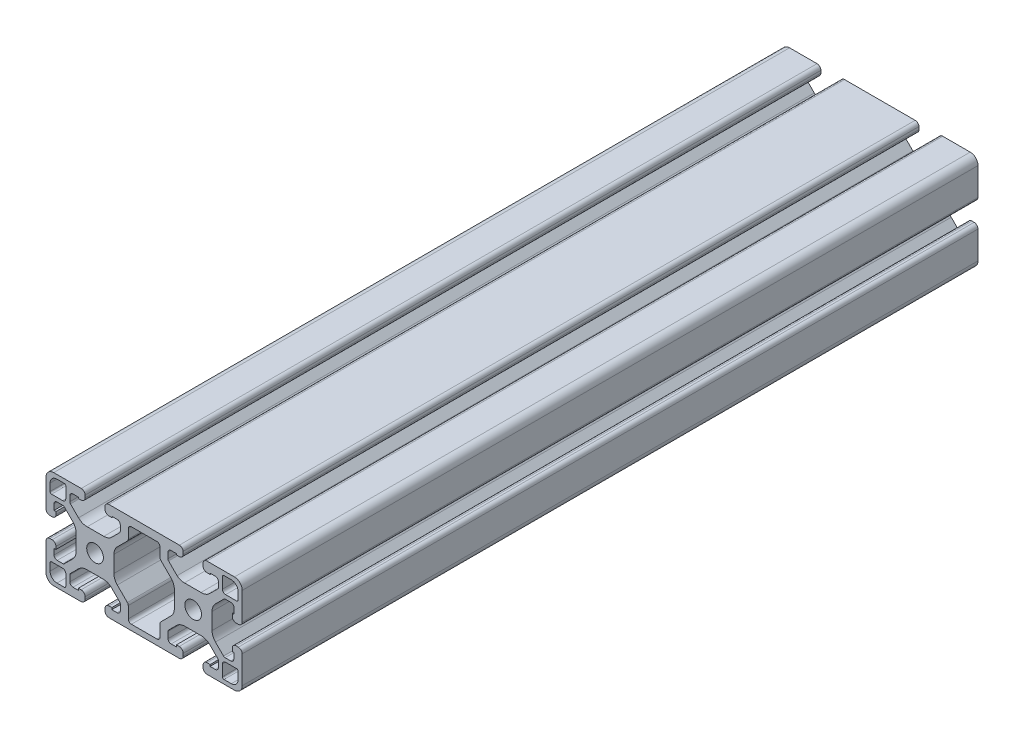
SolidWorks part; units mm, degrees
material "6105-T5 Aluminum"
ref_plane "Front Plane" through (0, 0, 0) normal (0, 0, 1) x (1, 0, 0)
ref_plane "Top Plane" through (0, 0, 0) normal (0, 1, 0) x (1, 0, 0)
ref_plane "Right Plane" through (0, 0, 0) normal (1, 0, 0) x (0, 0, -1)
sketch "Sketch1" plane through (0, 0, 0) normal (0, 0, 1) x (1, 0, 0)
  line L0 (0, 20) -> (0, -20) construction
  line L1 (-14.38, 20) -> (14.38, 20)
  line L2 (-30.0243, -12.1998) -> (-26.7392, -8.9146)
  line L3 (-15.94, 17.51) -> (-15.94, 18.6069)
  line L4 (-10.9397, -6.7352) -> (-6.8324, -10.8426)
  line L5 (-12.3247, 3.3825) -> (-12.3289, -3.3756)
  line L6 (-6.8214, 10.8451) -> (-10.9313, 6.7404)
  line L7 (-6.4494, 15.43) -> (-6.4494, 11.7432)
  line L8 (0, 16.6968) -> (-5.1794, 16.7)
  line L9 (-14.37, 15.94) -> (-13.1517, 15.94)
  line L10 (-13.1517, 16.4117) -> (-13.1517, 15.94)
  line L11 (-5.1904, -17.7174) -> (5.1904, -17.7174)
  line L12 (-6.4604, -16.4474) -> (-6.4604, -11.7406)
  line L13 (-13.1517, 16.4117) -> (-11.0437, 16.4117)
  line L14 (-9.715, 12.8476) -> (-9.715, 15.1433)
  line L15 (-13.4586, 8.7397) -> (-9.9761, 12.2179)
  line L16 (-23.1872, 7.7) -> (-16.4312, 7.7)
  line L17 (-37.72, 11.94) -> (-33.21, 11.94)
  line L18 (-31.935, 13.21) -> (-31.935, 17.72)
  line L19 (-35.545, 18.35) -> (-32.565, 18.35)
  line L20 (-38.345, 15.55) -> (-38.345, 12.57)
  line L21 (-26.7456, 9.087) -> (-30.0243, 12.3658)
  line L22 (-30.285, 12.9951) -> (-30.285, 15.0869)
  line L23 (-29.015, 16.3569) -> (-26.8483, 16.3569)
  line L24 (-26.8483, 16.3569) -> (-26.8483, 15.8852)
  line L25 (-26.8483, 15.8852) -> (-25.63, 15.8852)
  line L26 (-24.06, 17.4552) -> (-24.06, 18.43)
  line L27 (-36.83, 20) -> (-25.63, 20)
  line L28 (-31.935, -17.72) -> (-31.935, -13.21)
  line L29 (-40, 16.83) -> (-40, 13)
  line L30 (-40, 5.5719) -> (-40, 13)
  line L31 (-38.43, 4.06) -> (-37.51, 4.06)
  line L32 (-35.94, 5.63) -> (-35.94, 6.6964)
  line L33 (-36.715, 6.6964) -> (-35.94, 6.6964)
  line L34 (-36.715, 6.6964) -> (-36.715, 9.02)
  line L35 (-35.445, 10.29) -> (-33.1501, 10.29)
  line L36 (-32.5208, 10.0293) -> (-29.0912, 6.5998)
  line L37 (-27.7, 3.241) -> (-27.7, -3.241)
  line L38 (-32.5208, -10.0293) -> (-29.0912, -6.5998)
  line L39 (-35.445, -10.29) -> (-33.1501, -10.29)
  line L40 (-36.715, -9.02) -> (-36.715, -6.6964)
  line L41 (-35.94, -6.6964) -> (-36.715, -6.6964)
  line L42 (-35.94, -6.6964) -> (-35.94, -5.63)
  line L43 (-38.43, -4.06) -> (-37.51, -4.06)
  line L44 (-40, -16.83) -> (-40, -5.5719)
  line L45 (-37.72, -11.94) -> (-33.21, -11.94)
  line L46 (-36.83, -20) -> (-25.6944, -20)
  line L47 (-14.3056, -20) -> (-6.9396, -20)
  line L48 (-29.015, -16.5584) -> (-26.8283, -16.5584)
  line L49 (-24.06, -17.4474) -> (-24.06, -18.3656)
  line L50 (-26.8283, -15.813) -> (-25.6944, -15.813)
  line L51 (-26.8283, -16.5584) -> (-26.8283, -15.813)
  line L52 (-30.285, -15.2884) -> (-30.285, -12.8291)
  line L53 (25.63, 20) -> (34.2818, 20)
  line L54 (-23.3834, -7.5234) -> (-16.6166, -7.5234)
  line L55 (-13.2608, -8.9146) -> (-9.9757, -12.1998)
  line L56 (-9.715, -12.8291) -> (-9.715, -15.3686)
  line L57 (-13.1717, -16.5584) -> (-11.0293, -16.5584)
  line L58 (-13.1717, -16.5584) -> (-13.1717, -15.813)
  line L59 (-14.3056, -15.813) -> (-13.1717, -15.813)
  line L60 (-15.94, -17.4474) -> (-15.94, -18.3656)
  line L61 (-6.9396, -20) -> (6.9396, -20)
  line L62 (6.9396, -20) -> (14.3056, -20)
  line L63 (-39.8916, 0) -> (0, 0) construction
  line L64 (25.6944, -20) -> (34.3223, -20)
  line L65 (15.94, -17.4474) -> (15.94, -18.3656)
  line L66 (13.1717, -15.813) -> (14.3056, -15.813)
  line L67 (13.1717, -16.5584) -> (13.1717, -15.813)
  line L68 (11.0293, -16.5584) -> (13.1717, -16.5584)
  line L69 (9.715, -12.8291) -> (9.715, -15.3686)
  line L70 (9.9757, -12.1998) -> (13.2608, -8.9146)
  line L71 (23.3834, -7.5234) -> (16.6166, -7.5234)
  line L72 (30.0243, -12.1998) -> (26.7392, -8.9146)
  line L73 (30.285, -15.2884) -> (30.285, -12.8291)
  line L74 (26.907, -16.5584) -> (29.015, -16.5584)
  line L75 (26.907, -15.8852) -> (26.907, -16.5584)
  line L76 (25.63, -15.8852) -> (26.907, -15.8852)
  line L77 (24.06, -18.43) -> (24.06, -17.4552)
  line L78 (6.8214, 10.8451) -> (10.9313, 6.7404)
  line L79 (36.83, -20) -> (34.3223, -20)
  line L80 (40, -16.83) -> (40, -5.5696)
  line L81 (40, 5.5719) -> (40, 13)
  line L82 (37.51, -3.9996) -> (38.43, -3.9996)
  line L83 (35.94, -6.7799) -> (35.94, -5.5696)
  line L84 (36.5725, -6.7799) -> (35.94, -6.7799)
  line L85 (36.5725, -9.1555) -> (36.5725, -6.7799)
  line L86 (33.0076, -10.4255) -> (35.3025, -10.4255)
  line L87 (29.0891, -6.8716) -> (32.3778, -10.1644)
  line L88 (27.7, 3.241) -> (27.7, -3.515)
  line L89 (32.5208, 10.0293) -> (29.0912, 6.5998)
  line L90 (35.445, 10.29) -> (33.1501, 10.29)
  line L91 (36.715, 6.6964) -> (36.715, 9.02)
  line L92 (35.94, 6.6964) -> (36.715, 6.6964)
  line L93 (35.94, 5.63) -> (35.94, 6.6964)
  line L94 (38.43, 4.06) -> (37.51, 4.06)
  line L95 (38.345, -15.55) -> (38.345, -12.57)
  line L96 (40, 16.83) -> (40, 13)
  line L97 (34.2818, 20) -> (36.83, 20)
  line L98 (31.935, -17.72) -> (31.935, -13.21)
  line L99 (24.06, 17.4552) -> (24.06, 18.43)
  line L100 (26.8483, 15.8852) -> (25.63, 15.8852)
  line L101 (26.8483, 16.3569) -> (26.8483, 15.8852)
  line L102 (29.015, 16.3569) -> (26.8483, 16.3569)
  line L103 (30.285, 12.9951) -> (30.285, 15.0869)
  line L104 (26.7456, 9.087) -> (30.0243, 12.3658)
  line L105 (38.345, 15.55) -> (38.345, 12.57)
  line L106 (32.565, 18.35) -> (35.545, 18.35)
  line L107 (31.935, 13.21) -> (31.935, 17.72)
  line L108 (37.72, 11.94) -> (33.21, 11.94)
  line L109 (23.1872, 7.7) -> (16.4312, 7.7)
  line L110 (13.4586, 8.7397) -> (9.9761, 12.2179)
  line L111 (9.715, 12.8476) -> (9.715, 15.1433)
  line L112 (11.0437, 16.4117) -> (13.1517, 16.4117)
  line L113 (6.4604, -16.4474) -> (6.4604, -11.7406)
  line L114 (-38.345, -15.55) -> (-38.345, -12.57)
  line L115 (13.1517, 16.4117) -> (13.1517, 15.94)
  line L116 (13.1517, 15.94) -> (14.37, 15.94)
  line L117 (0, 16.6968) -> (5.1794, 16.7)
  line L118 (6.4494, 15.43) -> (6.4494, 11.7432)
  line L119 (-35.545, -18.35) -> (-32.565, -18.35)
  line L120 (12.3247, 3.3825) -> (12.3289, -3.3756)
  line L121 (10.9397, -6.7352) -> (6.8324, -10.8426)
  line L122 (15.94, 17.51) -> (15.94, 18.6069)
  line L129 (37.72, -11.94) -> (33.21, -11.94)
  line L131 (32.565, -18.35) -> (35.545, -18.35)
  line L133 (-20, 11.7412) -> (-20, -12.5149) construction
  line L134 (20, 12.6864) -> (20, -12.5149) construction
  line L135 (-20, 0) -> (-47.3415, -27.3415) construction
  arc A0 (-15.94, 18.6069) -> (-14.38, 20) centre (-14.38, 18.43) cw
  circle A1 centre (-20, 0) radius 3.4
  arc A2 (-14.37, 15.94) -> (-15.94, 17.51) centre (-14.37, 17.51) cw
  arc A3 (-11.0437, 16.4117) -> (-9.715, 15.1433) centre (-10.985, 15.1431) cw
  arc A4 (-13.4586, 8.7397) -> (-16.4312, 7.7) centre (-16.4245, 12.45) cw
  arc A5 (-23.1872, 7.7) -> (-26.7456, 9.087) centre (-23.3868, 12.4458) cw
  arc A6 (-12.3289, -3.3756) -> (-10.9397, -6.7352) centre (-7.5789, -3.3786) ccw
  arc A7 (-10.9313, 6.7404) -> (-12.3247, 3.3825) centre (-7.5747, 3.3795) ccw
  arc A8 (-6.8214, 10.8451) -> (-6.4494, 11.7432) centre (-7.7194, 11.7432) ccw
  arc A9 (-5.1794, 16.7) -> (-6.4494, 15.43) centre (-5.1794, 15.43) ccw
  arc A10 (-9.715, 12.8476) -> (-9.9761, 12.2179) centre (-10.605, 12.8476) cw
  arc A11 (-6.4604, -16.4474) -> (-5.1904, -17.7174) centre (-5.1904, -16.4474) ccw
  arc A12 (-6.4604, -11.7406) -> (-6.8324, -10.8426) centre (-7.7304, -11.7406) ccw
  arc A13 (-33.21, 11.94) -> (-31.935, 13.21) centre (-33.205, 13.21) ccw
  arc A14 (-31.935, 17.72) -> (-32.565, 18.35) centre (-32.565, 17.72) ccw
  arc A15 (-35.545, 18.35) -> (-38.345, 15.55) centre (-35.545, 15.55) ccw
  arc A16 (-38.345, 12.57) -> (-37.72, 11.94) centre (-37.715, 12.57) ccw
  arc A17 (-30.285, 12.9951) -> (-30.0243, 12.3658) centre (-29.395, 12.9951) ccw
  arc A18 (-29.015, 16.3569) -> (-30.285, 15.0869) centre (-29.015, 15.0869) ccw
  arc A19 (-25.63, 15.8852) -> (-24.06, 17.4552) centre (-25.63, 17.4552) ccw
  arc A20 (-24.06, 18.43) -> (-25.63, 20) centre (-25.63, 18.43) ccw
  arc A21 (-36.83, 20) -> (-40, 16.83) centre (-36.83, 16.83) ccw
  arc A22 (-40, 5.5719) -> (-38.43, 4.06) centre (-38.4311, 5.63) ccw
  arc A23 (-37.51, 4.06) -> (-35.94, 5.63) centre (-37.51, 5.63) ccw
  arc A24 (-35.445, 10.29) -> (-36.715, 9.02) centre (-35.445, 9.02) ccw
  arc A25 (-32.5208, 10.0293) -> (-33.1501, 10.29) centre (-33.1501, 9.4) ccw
  arc A26 (-27.7, 3.241) -> (-29.0912, 6.5998) centre (-32.45, 3.241) ccw
  arc A27 (-27.7, -3.241) -> (-29.0912, -6.5998) centre (-32.45, -3.241) cw
  arc A28 (-32.5208, -10.0293) -> (-33.1501, -10.29) centre (-33.1501, -9.4) cw
  arc A29 (-35.445, -10.29) -> (-36.715, -9.02) centre (-35.445, -9.02) cw
  arc A30 (-37.51, -4.06) -> (-35.94, -5.63) centre (-37.51, -5.63) cw
  arc A31 (-40, -5.5719) -> (-38.43, -4.06) centre (-38.4311, -5.63) cw
  arc A32 (-40, -16.83) -> (-36.83, -20) centre (-36.83, -16.83) ccw
  arc A33 (-24.06, -18.3656) -> (-25.6944, -20) centre (-25.6944, -18.3656) cw
  arc A34 (-25.6944, -15.813) -> (-24.06, -17.4474) centre (-25.6944, -17.4474) cw
  arc A35 (-30.285, -15.2884) -> (-29.015, -16.5584) centre (-29.015, -15.2884) ccw
  arc A36 (-30.0243, -12.1998) -> (-30.285, -12.8291) centre (-29.395, -12.8291) ccw
  arc A37 (-23.3834, -7.5234) -> (-26.7392, -8.9146) centre (-23.3804, -12.2734) ccw
  arc A38 (-13.2608, -8.9146) -> (-16.6166, -7.5234) centre (-16.6196, -12.2734) ccw
  arc A39 (-9.715, -12.8291) -> (-9.9757, -12.1998) centre (-10.605, -12.8291) ccw
  arc A40 (-11.0293, -16.5584) -> (-9.715, -15.3686) centre (-10.9825, -15.2892) ccw
  arc A41 (-14.3056, -15.813) -> (-15.94, -17.4474) centre (-14.3056, -17.4474) ccw
  arc A42 (-15.94, -18.3656) -> (-14.3056, -20) centre (-14.3056, -18.3656) ccw
  arc A43 (15.94, -18.3656) -> (14.3056, -20) centre (14.3056, -18.3656) cw
  arc A44 (14.3056, -15.813) -> (15.94, -17.4474) centre (14.3056, -17.4474) cw
  arc A45 (11.0293, -16.5584) -> (9.715, -15.3686) centre (10.9825, -15.2892) cw
  arc A46 (9.715, -12.8291) -> (9.9757, -12.1998) centre (10.605, -12.8291) cw
  arc A47 (13.2608, -8.9146) -> (16.6166, -7.5234) centre (16.6196, -12.2734) cw
  arc A48 (23.3834, -7.5234) -> (26.7392, -8.9146) centre (23.3804, -12.2734) cw
  arc A49 (30.0243, -12.1998) -> (30.285, -12.8291) centre (29.395, -12.8291) cw
  arc A50 (30.285, -15.2884) -> (29.015, -16.5584) centre (29.015, -15.2884) cw
  arc A51 (24.06, -17.4552) -> (25.63, -15.8852) centre (25.63, -17.4552) cw
  arc A52 (25.6944, -20) -> (24.06, -18.43) centre (25.63, -18.4313) cw
  arc A53 (40, -16.83) -> (36.83, -20) centre (36.83, -16.83) cw
  arc A54 (38.43, -3.9996) -> (40, -5.5696) centre (38.43, -5.5696) cw
  arc A55 (35.94, -5.5696) -> (37.51, -3.9996) centre (37.51, -5.5696) cw
  arc A56 (36.5725, -9.1555) -> (35.3025, -10.4255) centre (35.3025, -9.1555) cw
  arc A57 (33.0076, -10.4255) -> (32.3778, -10.1644) centre (33.0076, -9.5355) cw
  arc A58 (29.0891, -6.8716) -> (27.7, -3.515) centre (32.45, -3.515) cw
  arc A59 (27.7, 3.241) -> (29.0912, 6.5998) centre (32.45, 3.241) cw
  arc A60 (32.5208, 10.0293) -> (33.1501, 10.29) centre (33.1501, 9.4) cw
  arc A61 (35.445, 10.29) -> (36.715, 9.02) centre (35.445, 9.02) cw
  arc A62 (37.51, 4.06) -> (35.94, 5.63) centre (37.51, 5.63) cw
  arc A63 (40, 5.5719) -> (38.43, 4.06) centre (38.4311, 5.63) cw
  arc A64 (36.83, 20) -> (40, 16.83) centre (36.83, 16.83) cw
  arc A65 (24.06, 18.43) -> (25.63, 20) centre (25.63, 18.43) cw
  arc A66 (25.63, 15.8852) -> (24.06, 17.4552) centre (25.63, 17.4552) cw
  arc A67 (29.015, 16.3569) -> (30.285, 15.0869) centre (29.015, 15.0869) cw
  arc A68 (30.285, 12.9951) -> (30.0243, 12.3658) centre (29.395, 12.9951) cw
  arc A69 (38.345, 12.57) -> (37.72, 11.94) centre (37.715, 12.57) cw
  arc A70 (35.545, 18.35) -> (38.345, 15.55) centre (35.545, 15.55) cw
  arc A71 (31.935, 17.72) -> (32.565, 18.35) centre (32.565, 17.72) cw
  arc A72 (33.21, 11.94) -> (31.935, 13.21) centre (33.205, 13.21) cw
  arc A73 (6.4604, -11.7406) -> (6.8324, -10.8426) centre (7.7304, -11.7406) cw
  arc A74 (6.4604, -16.4474) -> (5.1904, -17.7174) centre (5.1904, -16.4474) cw
  arc A75 (9.715, 12.8476) -> (9.9761, 12.2179) centre (10.605, 12.8476) ccw
  arc A76 (5.1794, 16.7) -> (6.4494, 15.43) centre (5.1794, 15.43) cw
  arc A77 (6.8214, 10.8451) -> (6.4494, 11.7432) centre (7.7194, 11.7432) cw
  arc A78 (10.9313, 6.7404) -> (12.3247, 3.3825) centre (7.5747, 3.3795) cw
  arc A79 (12.3289, -3.3756) -> (10.9397, -6.7352) centre (7.5789, -3.3786) cw
  arc A80 (23.1872, 7.7) -> (26.7456, 9.087) centre (23.3868, 12.4458) ccw
  arc A81 (13.4586, 8.7397) -> (16.4312, 7.7) centre (16.4245, 12.45) ccw
  arc A82 (11.0437, 16.4117) -> (9.715, 15.1433) centre (10.985, 15.1431) ccw
  arc A83 (14.37, 15.94) -> (15.94, 17.51) centre (14.37, 17.51) ccw
  circle A84 centre (20, 0) radius 3.4
  arc A85 (15.94, 18.6069) -> (14.38, 20) centre (14.38, 18.43) ccw
  arc A86 (-38.345, -12.57) -> (-37.72, -11.94) centre (-37.715, -12.57) cw
  arc A87 (-35.545, -18.35) -> (-38.345, -15.55) centre (-35.545, -15.55) cw
  arc A88 (-31.935, -17.72) -> (-32.565, -18.35) centre (-32.565, -17.72) cw
  arc A89 (-33.21, -11.94) -> (-31.935, -13.21) centre (-33.205, -13.21) cw
  arc A90 (33.21, -11.94) -> (31.935, -13.21) centre (33.205, -13.21) ccw
  arc A91 (31.935, -17.72) -> (32.565, -18.35) centre (32.565, -17.72) ccw
  arc A92 (35.545, -18.35) -> (38.345, -15.55) centre (35.545, -15.55) ccw
  arc A93 (38.345, -12.57) -> (37.72, -11.94) centre (37.715, -12.57) ccw
  dimension "D2" = 6.8
  dimension "D1" = 40
  dimension "D3" = 40
  dimension "D4" = 8.12
  dimension "D5" = 80
  dimension "D6" = 3.3
  dimension "D7" = 12.3
  dimension "D8" = 45
  dimension "D9" = 20.57
  dimension "D10" = 4.06
  dimension "D15" = 1.5145
  dimension "D16" = 1.65
extrude "Extrude1" add sketch "Sketch1" against normal blind 300
